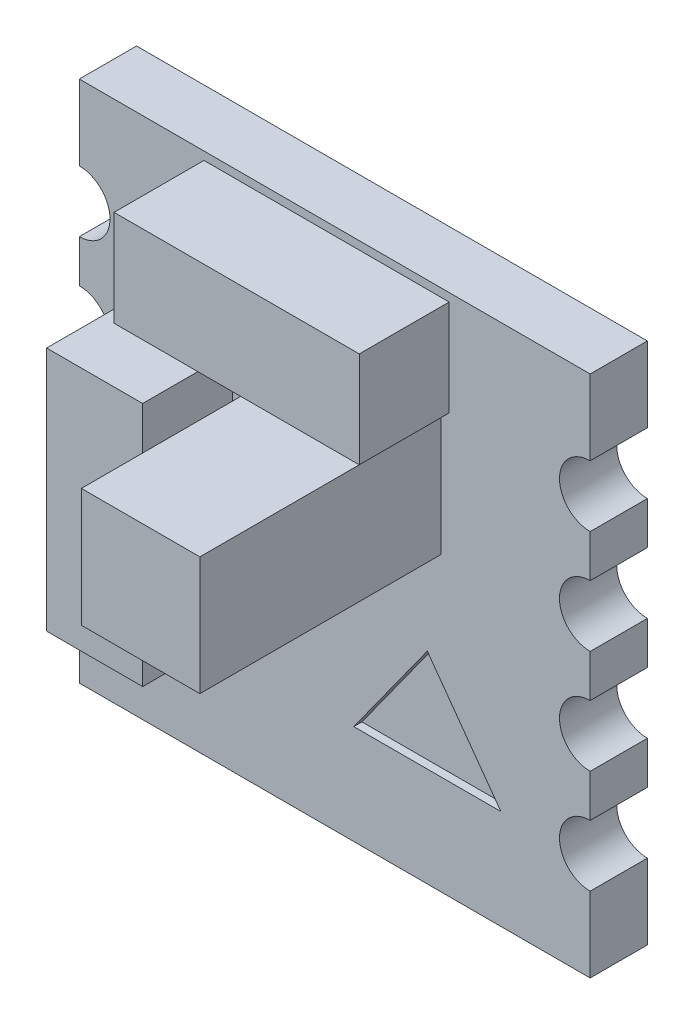
SolidWorks part; units mm, degrees
ref_plane "Front Plane" through (0, 0, 0) normal (0, 0, 1) x (1, 0, 0)
ref_plane "Top Plane" through (0, 0, 0) normal (0, 1, 0) x (1, 0, 0)
ref_plane "Right Plane" through (0, 0, 0) normal (1, 0, 0) x (0, 0, -1)
sketch "Sketch1" plane through (0, 0, 0) normal (0, 0, 1) x (1, 0, 0)
  line L1 (-6.25, 6.4) -> (6.25, 6.4)
  line L2 (-6.25, 6.4) -> (-6.25, -6.4)
  line L3 (-6.25, -6.4) -> (6.25, -6.4)
  line L4 (6.25, 6.4) -> (6.25, -6.4)
  line L5 (-6.25, 6.4) -> (6.25, -6.4) construction
  line L6 (-6.25, -6.4) -> (6.25, 6.4) construction
  point P0 (0, 0)
  dimension "D1" = 12.5
  dimension "D2" = 12.8
extrude "Boss-Extrude1" add sketch "Sketch1" along normal mid plane 1.4
sketch "Sketch2" plane through (0, 0, 0) normal (0, 0, 1) x (1, 0, 0)
  line L0 (0, 0) -> (-6.25, 0) construction
  line L1 (0, 0) -> (0, 6.4) construction
  line L2 (6.25, 6.4) -> (6.25, -6.4) construction
  line L4 (6.25, -6.4) -> (6.25, 6.4)
  line L5 (6.25, 6.4) -> (-6.25, 6.4)
  line L6 (-6.25, 6.4) -> (-6.25, -6.4)
  line L7 (-6.25, -6.4) -> (6.25, -6.4)
  line L8 (6.25, -6.4) -> (6.25, 6.4) construction
  line L9 (6.25, 6.4) -> (-6.25, 6.4) construction
  line L10 (-6.25, 6.4) -> (-6.25, -6.4) construction
  line L11 (-6.25, -6.4) -> (6.25, -6.4) construction
  circle A0 centre (-6.25, 1.27) radius 0.75
  circle A1 centre (-6.25, 3.81) radius 0.75
  circle A2 centre (-6.25, -1.27) radius 0.75
  circle A3 centre (-6.25, -3.81) radius 0.75
  circle A4 centre (6.25, -3.81) radius 0.75
  circle A5 centre (6.25, -1.27) radius 0.75
  circle A6 centre (6.25, 3.81) radius 0.75
  circle A7 centre (6.25, 1.27) radius 0.75
  dimension "D4" = 1.5
  dimension "D5" = 1.5
  dimension "D2" = 1.27
  dimension "D3" = 2.54
  dimension "D1" = 0
extrude "Cut-Extrude1" cut sketch "Sketch2" against normal through all both and the other way through all
sketch "Sketch3" plane through (0, 0, 0.7) normal (0, 0, 1) x (1, 0, 0)
  line L0 (6.25, 4.56) -> (6.25, 6.4) construction
  line L1 (-3.2, 6.2) -> (2.8, 6.2)
  line L2 (-3.2, 6.2) -> (-3.2, 3.85)
  line L3 (-3.2, 3.85) -> (2.8, 3.85)
  line L4 (2.8, 6.2) -> (2.8, 3.85)
  line L5 (-3.2, 6.2) -> (2.8, 3.85) construction
  line L6 (-3.2, 3.85) -> (2.8, 6.2) construction
  line L7 (-4.85, 2.5) -> (-2.5, 2.5)
  line L8 (-4.85, 2.5) -> (-4.85, -3.5)
  line L9 (-4.85, -3.5) -> (-2.5, -3.5)
  line L10 (-2.5, 2.5) -> (-2.5, -3.5)
  line L11 (-4.85, 2.5) -> (-2.5, -3.5) construction
  line L12 (-4.85, -3.5) -> (-2.5, 2.5) construction
  line L13 (6.25, 6.4) -> (-6.25, 6.4) construction
  line L14 (-6.25, 3.06) -> (-6.25, 2.02) construction
  point P0 (-0.2, 5.025)
  point P5 (-3.675, -0.5)
  dimension "D1" = 2.35
  dimension "D2" = 6
  dimension "D3" = 2.35
  dimension "D4" = 6
  dimension "D5" = 3.45
  dimension "D6" = 0.2
  dimension "D7" = 1.4
  dimension "D8" = 3.9
extrude "Boss-Extrude2" add sketch "Sketch3" along normal blind 2.2
sketch "Sketch4" plane through (0, 0, 0.7) normal (0, 0, 1) x (1, 0, 0)
  line L0 (6.25, 2.02) -> (6.25, 3.06) construction
  line L1 (-0.3, 3.65) -> (2.6, 3.65)
  line L2 (-0.3, 3.65) -> (-0.3, 0.75)
  line L3 (-0.3, 0.75) -> (2.6, 0.75)
  line L4 (2.6, 3.65) -> (2.6, 0.75)
  line L5 (-0.3, 3.65) -> (2.6, 0.75) construction
  line L6 (-0.3, 0.75) -> (2.6, 3.65) construction
  line L7 (-3.2, 3.85) -> (2.8, 3.85) construction
  point P0 (1.15, 2.2)
  dimension "D1" = 2.9
  dimension "D2" = 2.9
  dimension "D3" = 3.65
  dimension "D4" = 0.2
extrude "Boss-Extrude3" add sketch "Sketch4" along normal offset from surface (5.9 mm away) 7.3 up to face at (0, 0, -0.7)
sketch "Sketch5" plane through (0, 0, 0) normal (0, 0, 1) x (1, 0, 0)
  point P0 (0, 0)
sketch "Sketch6" plane through (0, 0, 0.7) normal (0, 0, 1) x (1, 0, 0)
  line L0 (2.2654, -1.465) -> (0.4654, -3.965)
  line L1 (0.4654, -3.965) -> (4.0654, -3.965)
  line L2 (2.2654, -3.965) -> (2.2654, -1.465)
  line L3 (2.2654, -1.465) -> (4.0654, -3.965)
  dimension "D1" = 2.5
  dimension "D2" = 1.8
extrude "Cut-Extrude2" cut sketch "Sketch6" against normal blind 0.2 contours L1 L2 L0 | L3 L2 L1
